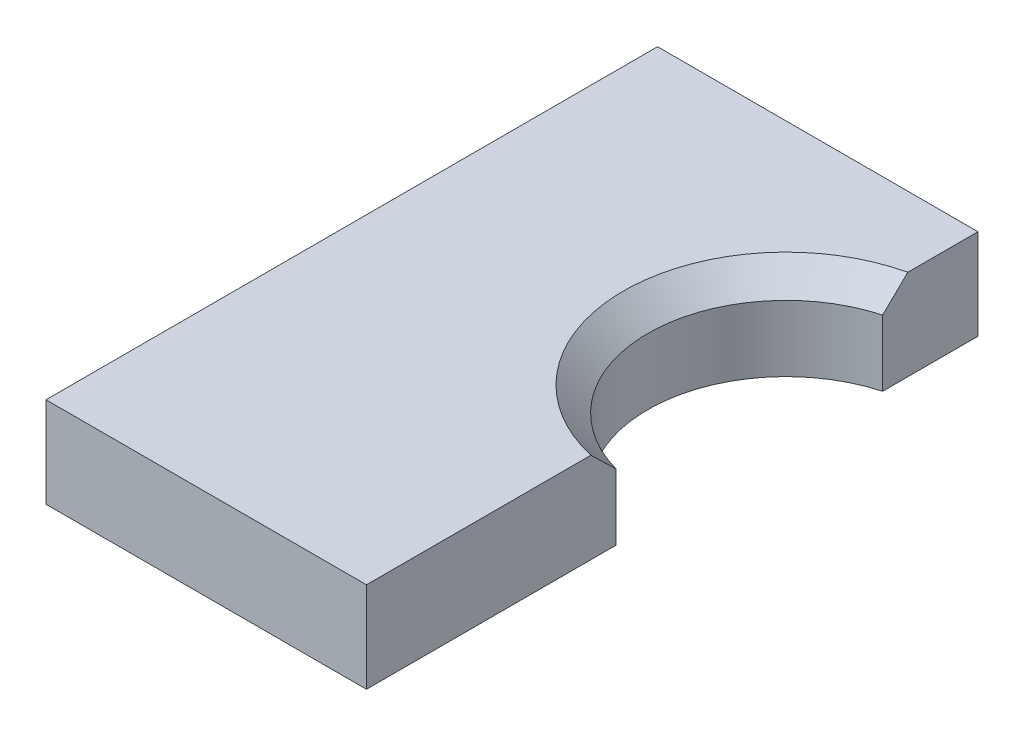
SolidWorks part; units mm, degrees
ref_plane "Front Plane" through (0, 0, 0) normal (0, 0, 1) x (1, 0, 0)
ref_plane "Top Plane" through (0, 0, 0) normal (0, 1, 0) x (1, 0, 0)
ref_plane "Right Plane" through (0, 0, 0) normal (1, 0, 0) x (0, 0, -1)
sketch "Sketch1" plane through (0, 0, 0) normal (0, 1, 0) x (1, 0, 0)
  line L0 (0, 0) -> (14.6, 0) construction
  line L1 (0, 0) -> (13.1, 0)
  line L2 (0, 0) -> (0, 28.9972)
  line L3 (0, 28.9972) -> (13.1, 28.9972)
  line L4 (13.1, 0) -> (13.1, 28.9972)
  line L5 (14.6, 0) -> (14.6, 19.65) construction
  line L6 (14.6, 14) -> (14.6, 19.65) construction
  line L7 (13.1, 28.9972) -> (13.1, 25.0972)
  line L8 (0, 4) -> (13.1, 4)
  line L9 (14.6, 19.65) -> (8.95, 19.65) construction
  circle A0 centre (14.6, 19.65) radius 5.65
  dimension "D2" = 11.3
  dimension "D1" = 1.5
  dimension "D3" = 14
  dimension "D4" = 13.1
  dimension "D5" = 3.9
  dimension "D6" = 4
  dimension "D7" = 4.15
extrude "Boss-Extrude1" add sketch "Sketch1" along normal blind 3.7 contours A0 L4 L3 L2 L8
chamfer "Chamfer1" distance 1 angle 45 1 edges at (8.95, 3.7, -19.65)
